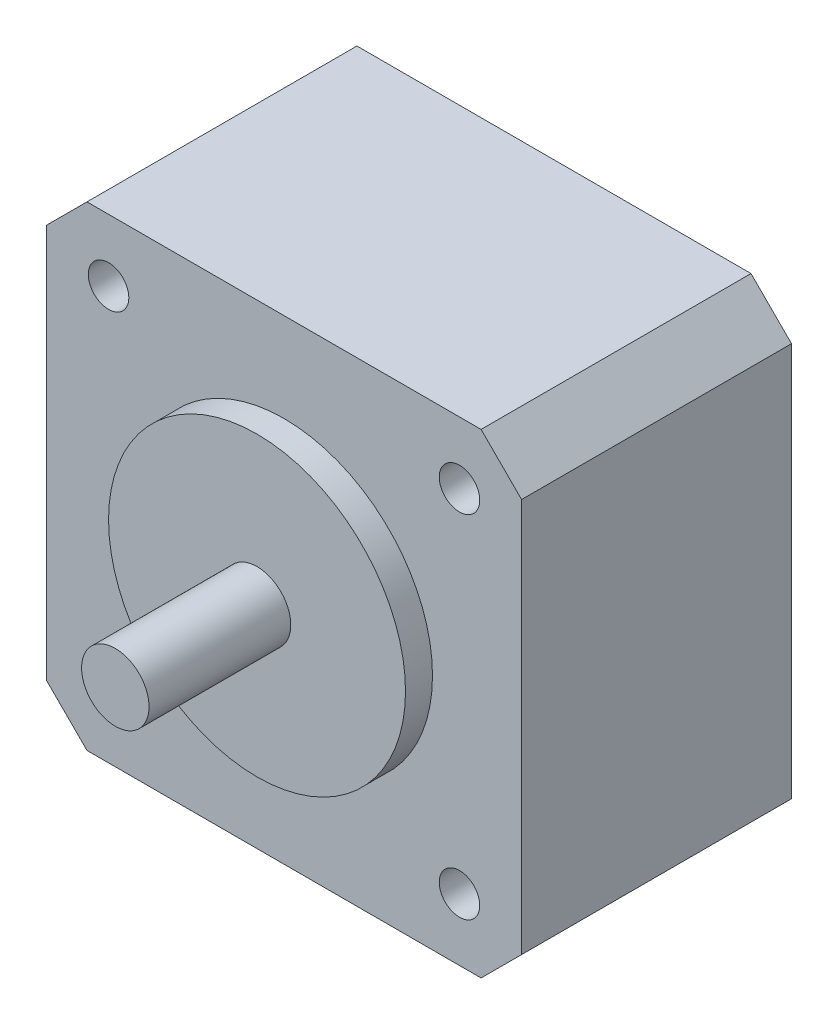
SolidWorks part; units mm, degrees
material "1060 Alloy"
ref_plane "Front Plane" through (0, 0, 0) normal (0, 0, 1) x (1, 0, 0)
ref_plane "Top Plane" through (0, 0, 0) normal (0, 1, 0) x (1, 0, 0)
ref_plane "Right Plane" through (0, 0, 0) normal (1, 0, 0) x (0, 0, -1)
sketch "Sketch1" plane through (0, 0, 0) normal (0, 0, 1) x (1, 0, 0)
  line L1 (-17.6, 17.6) -> (17.6, 17.6)
  line L2 (-17.6, 17.6) -> (-17.6, -17.6)
  line L3 (-17.6, -17.6) -> (17.6, -17.6)
  line L4 (17.6, 17.6) -> (17.6, -17.6)
  line L5 (-17.6, 17.6) -> (17.6, -17.6) construction
  line L6 (-17.6, -17.6) -> (17.6, 17.6) construction
  point P0 (0, 0)
  dimension "D1" = 35.2
  dimension "D2" = 35.2
extrude "Boss-Extrude1" add sketch "Sketch1" along normal blind 20
sketch "Sketch2" plane through (0, 0, 20) normal (0, 0, 1) x (1, 0, 0)
  circle A0 centre (0, 0) radius 11
  dimension "D1" = 22
extrude "Boss-Extrude2" add sketch "Sketch2" along normal blind 2
sketch "Sketch3" plane through (0, 0, 22) normal (0, 0, 1) x (1, 0, 0)
  circle A0 centre (0, 0) radius 2.5
  dimension "D1" = 5
extrude "Boss-Extrude3" add sketch "Sketch3" along normal blind 10.5
sketch "Sketch4" plane through (0, 0, 20) normal (0, 0, 1) x (1, 0, 0)
  line L0 (-13, 13) -> (13, -13) construction
  circle A0 centre (13, 13) radius 1.5
  circle A1 centre (13, -13) radius 1.5
  circle A2 centre (-13, -13) radius 1.5
  circle A3 centre (-13, 13) radius 1.5
  point P8 (0, 0)
  dimension "D3" = 3
  dimension "D4" = 3
  dimension "D5" = 3
  dimension "D6" = 3
  dimension "D1" = 26
  dimension "D2" = 26
extrude "Cut-Extrude1" cut sketch "Sketch4" against normal blind 4.5
chamfer "Chamfer1" distance 3 angle 45 4 edges at (-17.6, -17.6, 10) (-17.6, 17.6, 10) (17.6, -17.6, 10) (17.6, 17.6, 10)
